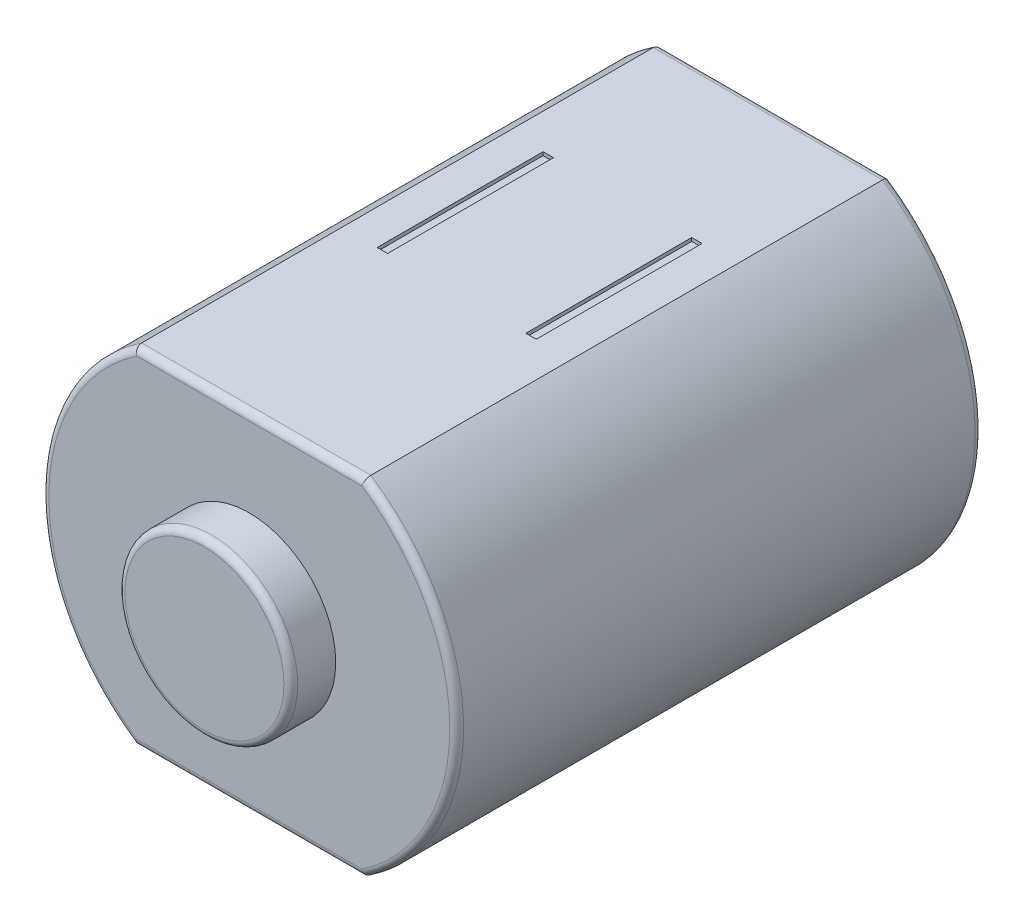
SolidWorks part; units mm, degrees
ref_plane "Ebene vorne" through (0, 0, 0) normal (0, 0, 1) x (1, 0, 0)
ref_plane "Ebene oben" through (0, 0, 0) normal (0, 1, 0) x (1, 0, 0)
ref_plane "Ebene rechts" through (0, 0, 0) normal (1, 0, 0) x (0, 0, -1)
sketch "Skizze1" plane through (0, 0, 0) normal (0, 0, 1) x (1, 0, 0)
  line L1 (-3.3166, 5) -> (3.3166, 5)
  line L3 (-3.3166, -5) -> (3.3166, -5)
  line L5 (-6, 5) -> (6, -5) construction
  line L6 (-6, -5) -> (6, 5) construction
  arc A0 (-3.3166, 5) -> (-3.3166, -5) centre (0, 0) ccw
  arc A1 (3.3166, -5) -> (3.3166, 5) centre (0, 0) ccw
  point P0 (0, 0)
  dimension "D3" = 12
  dimension "D1" = 10
  dimension "D2" = 12
extrude "Aufsatz-Linear austragen1" add sketch "Skizze1" along normal blind 15.2
sketch "Skizze2" plane through (0, 0, 15.2) normal (0, 0, 1) x (1, 0, 0)
  circle A0 centre (0, 0) radius 2.5
  dimension "D1" = 5
extrude "Aufsatz-Linear austragen2" add sketch "Skizze2" along normal blind 1.3
sketch "Skizze3" plane through (0, 0, 0) normal (0, 0, -1) x (-1, 0, 0)
  circle A0 centre (0, 0) radius 0.5
  dimension "D1" = 1
extrude "Aufsatz-Linear austragen3" add sketch "Skizze3" along normal blind 2
fillet "Verrundung1" radius 0.2 9 edges at (2.5, 0, 16.5) (0, 5, 15.2) (6, 0, 15.2) (0, -5, 15.2) (-6, 0, 15.2) (0, -5, 0) (-6, 0, 0) (0, 5, 0) (6, 0, 0)
sketch "Skizze4" plane through (0, 5, 0) normal (0, 1, 0) x (1, 0, 0)
  line L0 (0, 0) -> (0, -15) construction
  line L1 (-2.3, -4.4) -> (-2, -4.4)
  line L2 (-2.3, -4.4) -> (-2.3, -9.2)
  line L3 (-2.3, -9.2) -> (-2, -9.2)
  line L4 (-2, -4.4) -> (-2, -9.2)
  line L5 (-3.3166, -15) -> (3.3166, -15) construction
  line L6 (3.2558, -15.2) -> (-3.2558, -15.2) construction
  line L7 (2, -4.4) -> (2, -9.2)
  line L8 (2.3, -9.2) -> (2, -9.2)
  line L9 (2.3, -4.4) -> (2.3, -9.2)
  line L10 (2.3, -4.4) -> (2, -4.4)
  dimension "D1" = 6
  dimension "D2" = 4.8
  dimension "D3" = 0.3
  dimension "D4" = 4
extrude "Schnitt-Linear austragen1" cut sketch "Skizze4" against normal blind 0.1
ref_plane "Ebene1" through (0, 0, 0) normal (0, 1, 0) x (1, 0, 0)
mirror "Spiegeln1" about plane through (0, 0, 0) normal (0, 1, 0) of "Schnitt-Linear austragen1"
